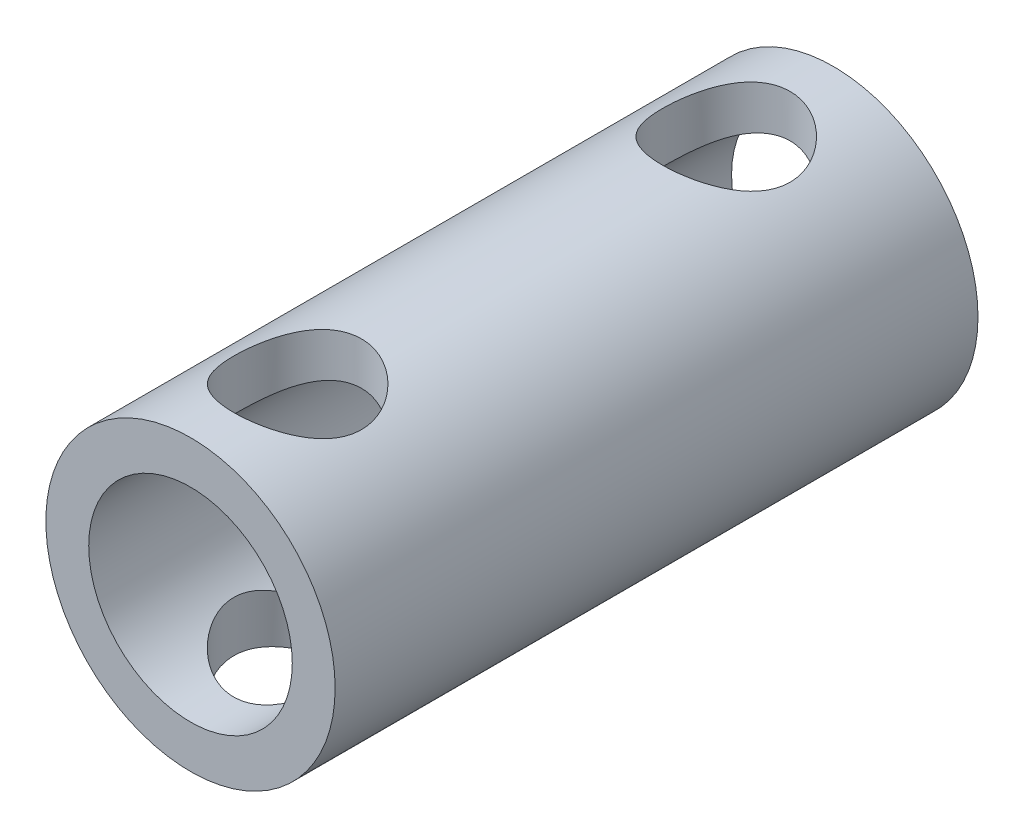
SolidWorks part; units mm, degrees
material "6061-T6 (SS)"
ref_plane "Front Plane" through (0, 0, 0) normal (0, 0, 1) x (1, 0, 0)
ref_plane "Top Plane" through (0, 0, 0) normal (0, 1, 0) x (1, 0, 0)
ref_plane "Right Plane" through (0, 0, 0) normal (1, 0, 0) x (0, 0, -1)
sketch "Sketch1" plane through (0, 0, 0) normal (0, 0, 1) x (1, 0, 0)
  circle A0 centre (0, 0) radius 2.3749
  circle A1 centre (0, 0) radius 3.375
  dimension "D1" = 4.7498
  dimension "D2" = 6.75
extrude "Boss-Extrude1" add sketch "Sketch1" along normal mid plane 15
sketch "Sketch2" plane through (0, 0, 0) normal (0, 1, 0) x (1, 0, 0)
  line L1 (-3.375, -7.5) -> (3.375, -7.5) construction
  circle A0 centre (0, -5) radius 1.49
  dimension "D1" = 2.98
  dimension "D2" = 2.5
extrude "Cut-Extrude1" cut sketch "Sketch2" against normal mid plane 25
mirror "Mirror1" about plane through (0, 0, 0) normal (0, 0, 1) of "Cut-Extrude1"
